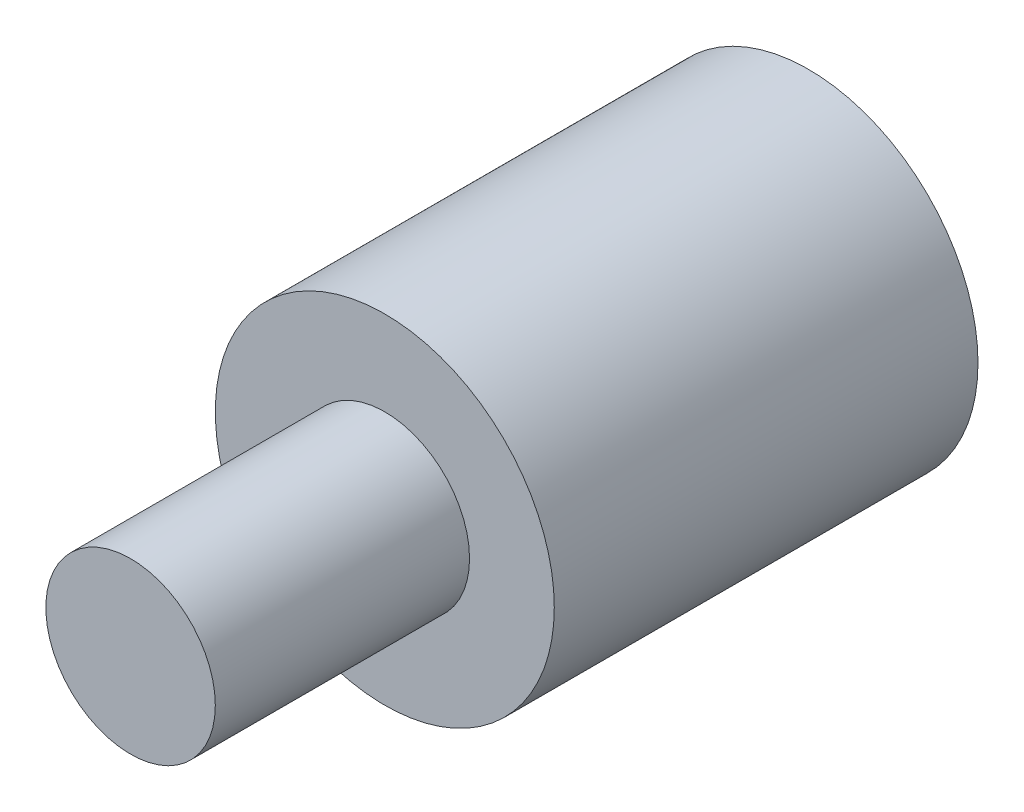
SolidWorks part; units mm, degrees
ref_plane "Front Plane" through (0, 0, 0) normal (0, 0, 1) x (1, 0, 0)
ref_plane "Top Plane" through (0, 0, 0) normal (0, 1, 0) x (1, 0, 0)
ref_plane "Right Plane" through (0, 0, 0) normal (1, 0, 0) x (0, 0, -1)
sketch "Sketch1" plane through (0, 0, 0) normal (0, 0, 1) x (1, 0, 0)
  circle A0 centre (0, 0) radius 20
  dimension "D1" = 40
extrude "Boss-Extrude1" add sketch "Sketch1" along normal blind 50 contours A0
sketch "Sketch4" plane through (0, 0, 50) normal (0, 0, 1) x (1, 0, 0)
  circle A0 centre (0, 0) radius 10
  dimension "D1" = 20
extrude "Boss-Extrude2" add sketch "Sketch4" along normal blind 30
